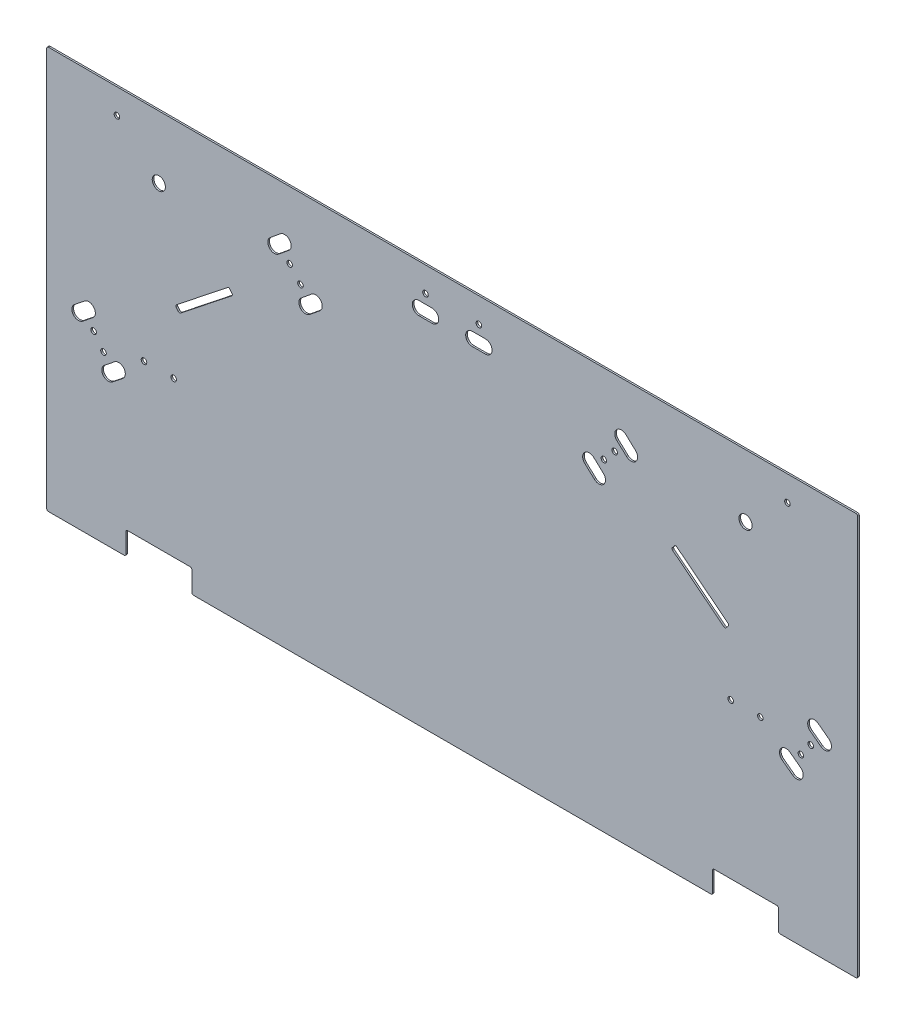
SolidWorks part; units mm, degrees
material "PE High Density"
ref_plane "Front Plane" through (0, 0, 0) normal (0, 0, 1) x (1, 0, 0)
ref_plane "Top Plane" through (0, 0, 0) normal (0, 1, 0) x (1, 0, 0)
ref_plane "Right Plane" through (0, 0, 0) normal (1, 0, 0) x (0, 0, -1)
sketch "Sketch1" plane through (0, 0, 0) normal (0, 0, 1) x (1, 0, 0)
  line L1 (-781.05, 387.35) -> (781.05, 387.35)
  line L2 (-781.05, 387.35) -> (-781.05, -387.35)
  line L3 (-781.05, -387.35) -> (781.05, -387.35)
  line L4 (781.05, 387.35) -> (781.05, -387.35)
  line L5 (-781.05, 387.35) -> (781.05, -387.35) construction
  line L6 (-781.05, -387.35) -> (781.05, 387.35) construction
  line L7 (-533.6334, 78.9622) -> (-525.7417, 69.0118)
  line L8 (-542.925, 342.9) -> (-542.925, -501.65) construction
  line L9 (542.925, 342.9) -> (542.925, -501.65) construction
  line L11 (587.375, 342.9) -> (587.375, -501.65) construction
  line L12 (-587.375, 342.9) -> (-587.375, -501.65) construction
  line L21 (-628.65, -387.35) -> (-501.65, -387.35)
  line L22 (-628.65, -387.35) -> (-628.65, -342.9)
  line L23 (-628.65, -342.9) -> (-501.65, -342.9)
  line L24 (-501.65, -387.35) -> (-501.65, -342.9)
  line L25 (628.65, -387.35) -> (501.65, -387.35)
  line L26 (628.65, -387.35) -> (628.65, -342.9)
  line L27 (628.65, -342.9) -> (501.65, -342.9)
  line L28 (501.65, -387.35) -> (501.65, -342.9)
  line L32 (-525.7417, 69.0118) -> (-422.2573, 151.0856)
  line L33 (-422.2573, 151.0856) -> (-430.149, 161.036)
  line L34 (-430.149, 161.036) -> (-533.6334, 78.9622)
  line L36 (525.8301, 69.1038) -> (422.2669, 151.078)
  line L37 (422.2669, 151.078) -> (430.149, 161.036)
  line L38 (430.149, 161.036) -> (533.7123, 79.0618)
  line L39 (533.7123, 79.0618) -> (525.8301, 69.1038)
  circle A0 centre (-51.435, 339.4592) radius 5.3578
  circle A1 centre (51.435, 339.3385) radius 5.3578
  circle A6 centre (-645.795, 339.09) radius 5.3578
  circle A7 centre (645.795, 339.09) radius 5.3578
  circle A11 centre (536.575, -44.45) radius 5.3578
  circle A12 centre (593.725, -44.45) radius 5.3578
  circle A13 centre (-593.725, -44.45) radius 5.3578
  circle A14 centre (-536.575, -44.45) radius 5.3578
  point P0 (0, 0)
  dimension "D3" = 10.7156
  dimension "D4" = 10.7156
  dimension "D7" = 729.615
  dimension "D8" = 729.615
  dimension "D19" = 135.255
  dimension "D20" = 48.26
  dimension "D21" = 10.7156
  dimension "D22" = 135.255
  dimension "D23" = 48.26
  dimension "D38" = 342.9
  dimension "D39" = 342.9
  dimension "D40" = 6.35
  dimension "D9" = 47.8908
  dimension "D14" = 350.901
  dimension "D24" = 10.7156
  dimension "D31" = 10.7156
  dimension "D32" = 10.7156
  dimension "D33" = 10.7156
  dimension "D34" = 10.7156
  dimension "D1" = 774.7
  dimension "D2" = 1562.1
  dimension "D10" = 48.0115
  dimension "D11" = 226.314
  dimension "D12" = 350.901
  dimension "D13" = 226.314
  dimension "D35" = 6.35
  dimension "D36" = 6.35
  dimension "D37" = 342.9
  dimension "D41" = 342.9
  dimension "D42" = 6.35
  dimension "D52" = 152.4
  dimension "D53" = 127
  dimension "D54" = 44.45
  dimension "D55" = 152.4
  dimension "D56" = 127
  dimension "D57" = 44.45
  dimension "D63" = 132.08
  dimension "D64" = 12.7
  dimension "D65" = 132.08
  dimension "D66" = 12.7
extrude "Boss-Extrude1" add sketch "Sketch1" along normal blind 3.175
sketch "Sketch2" plane through (0, 0, 3.175) normal (0, 0, 1) x (1, 0, 0)
  line L2 (781.05, 387.35) -> (781.05, -387.35) construction
  line L3 (628.65, -387.35) -> (781.05, -387.35) construction
  line L4 (-781.05, 387.35) -> (781.05, 387.35) construction
  line L5 (-781.05, 387.35) -> (-781.05, -387.35) construction
  line L7 (-781.05, -387.35) -> (-628.65, -387.35) construction
  circle A0 centre (-313.055, 258.318) radius 5.3578
  circle A1 centre (-292.227, 234.3543) radius 5.3578
  circle A2 centre (-690.753, -42.672) radius 5.3578
  circle A3 centre (-671.703, -68.072) radius 5.3578
  circle A4 centre (292.227, 234.3543) radius 5.3578
  circle A5 centre (313.055, 258.318) radius 5.3578
  circle A6 centre (690.753, -42.672) radius 5.3578
  circle A7 centre (671.703, -68.072) radius 5.3578
  dimension "D1" = 10.7156
  dimension "D3" = 31.75
  dimension "D8" = 129.032
  dimension "D2" = 90.297
  dimension "D4" = 344.678
  dimension "D5" = 109.347
  dimension "D6" = 31.75
  dimension "D7" = 467.995
  dimension "D9" = 488.823
  dimension "D10" = 467.995
  dimension "D11" = 488.823
  dimension "D12" = 129.032
  dimension "D13" = 31.75
  dimension "D14" = 90.297
  dimension "D15" = 109.347
  dimension "D16" = 344.678
  dimension "D17" = 31.75
extrude "Cut-Extrude1" cut sketch "Sketch2" against normal through all
sketch "Sketch3" plane through (0, 0, 3.175) normal (0, 0, 1) x (1, 0, 0)
  line L0 (-64.135, 308.9792) -> (-38.735, 308.9792) construction
  line L1 (-64.135, 321.6792) -> (-38.735, 321.6792)
  line L2 (-64.135, 296.2792) -> (-38.735, 296.2792)
  line L3 (38.735, 308.9792) -> (64.135, 308.9792) construction
  line L4 (38.735, 321.6792) -> (64.135, 321.6792)
  line L5 (38.735, 296.2792) -> (64.135, 296.2792)
  line L6 (-342.4859, 273.572) -> (-322.8733, 289.7122) construction
  line L7 (-350.556, 283.3784) -> (-330.9434, 299.5185)
  line L8 (-334.4159, 263.7657) -> (-314.8032, 279.9059)
  line L9 (-282.6651, 202.7491) -> (-263.0525, 218.8893) construction
  line L10 (-290.7352, 212.5554) -> (-271.1226, 228.6956)
  line L11 (-274.595, 192.9428) -> (-254.9824, 209.083)
  line L12 (-719.9479, -26.9932) -> (-700.1126, -11.1275) construction
  line L13 (-727.8807, -17.0755) -> (-708.0454, -1.2098)
  line L14 (-712.015, -36.9108) -> (-692.1797, -21.0451)
  line L15 (-662.2696, -99.5575) -> (-642.4343, -83.6918) construction
  line L16 (-670.2025, -89.6398) -> (-650.3672, -73.7742)
  line L17 (-654.3368, -109.4752) -> (-634.5015, -93.6095)
  line L18 (325.9271, 287.9302) -> (344.5749, 270.6843) construction
  line L19 (334.55, 297.2541) -> (353.1978, 280.0082)
  line L20 (317.3041, 278.6063) -> (335.952, 261.3604)
  line L21 (264.0577, 218.8893) -> (282.7056, 201.6434) construction
  line L22 (272.6807, 228.2132) -> (291.3285, 210.9673)
  line L23 (255.4348, 209.5654) -> (274.0826, 192.3195)
  line L24 (643.2495, -84.8267) -> (663.5646, -100.0734) construction
  line L25 (650.8729, -74.6692) -> (671.1879, -89.9158)
  line L26 (635.6262, -94.9843) -> (655.9413, -110.2309)
  line L27 (697.5841, -9.6895) -> (717.8992, -24.9361) construction
  line L28 (705.2074, 0.468) -> (725.5225, -14.7786)
  line L29 (689.9608, -19.847) -> (710.2758, -35.0936)
  line L30 (-781.05, 387.35) -> (781.05, 387.35) construction
  arc A0 (-64.135, 321.6792) -> (-64.135, 296.2792) centre (-64.135, 308.9792) ccw
  arc A1 (-38.735, 296.2792) -> (-38.735, 321.6792) centre (-38.735, 308.9792) ccw
  arc A2 (38.735, 321.6792) -> (38.735, 296.2792) centre (38.735, 308.9792) ccw
  arc A3 (64.135, 296.2792) -> (64.135, 321.6792) centre (64.135, 308.9792) ccw
  arc A4 (-350.556, 283.3784) -> (-334.4159, 263.7657) centre (-342.4859, 273.572) ccw
  arc A5 (-314.8032, 279.9059) -> (-330.9434, 299.5185) centre (-322.8733, 289.7122) ccw
  arc A6 (-290.7352, 212.5554) -> (-274.595, 192.9428) centre (-282.6651, 202.7491) ccw
  arc A7 (-254.9824, 209.083) -> (-271.1226, 228.6956) centre (-263.0525, 218.8893) ccw
  arc A8 (-727.8807, -17.0755) -> (-712.015, -36.9108) centre (-719.9479, -26.9932) ccw
  arc A9 (-692.1797, -21.0451) -> (-708.0454, -1.2098) centre (-700.1126, -11.1275) ccw
  arc A10 (-670.2025, -89.6398) -> (-654.3368, -109.4752) centre (-662.2696, -99.5575) ccw
  arc A11 (-634.5015, -93.6095) -> (-650.3672, -73.7742) centre (-642.4343, -83.6918) ccw
  arc A12 (334.55, 297.2541) -> (317.3041, 278.6063) centre (325.9271, 287.9302) ccw
  arc A13 (335.952, 261.3604) -> (353.1978, 280.0082) centre (344.5749, 270.6843) ccw
  arc A14 (272.6807, 228.2132) -> (255.4348, 209.5654) centre (264.0577, 218.8893) ccw
  arc A15 (274.0826, 192.3195) -> (291.3285, 210.9673) centre (282.7056, 201.6434) ccw
  arc A16 (650.8729, -74.6692) -> (635.6262, -94.9843) centre (643.2495, -84.8267) ccw
  arc A17 (655.9413, -110.2309) -> (671.1879, -89.9158) centre (663.5646, -100.0734) ccw
  arc A18 (705.2074, 0.468) -> (689.9608, -19.847) centre (697.5841, -9.6895) ccw
  arc A19 (710.2758, -35.0936) -> (725.5225, -14.7786) centre (717.8992, -24.9361) ccw
  circle A20 centre (-51.435, 339.4592) radius 5.3578 construction
  circle A21 centre (-313.055, 258.318) radius 5.3578 construction
  circle A22 centre (-292.227, 234.3543) radius 5.3578 construction
  circle A23 centre (-690.753, -42.672) radius 5.3578 construction
  circle A24 centre (-671.703, -68.072) radius 5.3578 construction
  circle A25 centre (292.227, 234.3543) radius 5.3578 construction
  circle A26 centre (313.055, 258.318) radius 5.3578 construction
  circle A27 centre (671.703, -68.072) radius 5.3578 construction
  circle A28 centre (690.753, -42.672) radius 5.3578 construction
  point P2 (-51.435, 308.9792)
  point P7 (51.435, 308.9792)
  point P14 (-332.6796, 281.6421)
  point P21 (-272.8588, 210.8192)
  point P28 (-710.0302, -19.0603)
  point P35 (-652.352, -91.6247)
  point P42 (335.251, 279.3073)
  point P49 (273.3817, 210.2664)
  point P56 (653.4071, -92.45)
  point P63 (707.7416, -17.3128)
  dimension "D3" = 17.78
  dimension "D5" = 17.78
  dimension "D1" = 25.4
  dimension "D2" = 25.4
  dimension "D4" = 17.78
  dimension "D6" = 17.78
  dimension "D7" = 17.78
  dimension "D8" = 17.78
  dimension "D9" = 17.78
  dimension "D10" = 17.78
  dimension "D11" = 17.78
extrude "Cut-Extrude2" cut sketch "Sketch3" against normal through all
fillet "Fillet1" radius 3.175 20 edges at (-525.7417, 69.0118, 1.5875) (-533.6334, 78.9622, 1.5875) (-430.149, 161.036, 1.5875) (-422.2573, 151.0856, 1.5875) (-628.65, -342.9, 1.5875) (-501.65, -342.9, 1.5875) (628.65, -342.9, 1.5875) (501.65, -342.9, 1.5875) (525.8301, 69.1038, 1.5875) (533.7123, 79.0618, 1.5875) (430.149, 161.036, 1.5875) (422.2669, 151.078, 1.5875) (-781.05, 387.35, 1.5875) (-781.05, -387.35, 1.5875) (-628.65, -387.35, 1.5875) (-501.65, -387.35, 1.5875) (501.65, -387.35, 1.5875) (628.65, -387.35, 1.5875) (781.05, -387.35, 1.5875) (781.05, 387.35, 1.5875)
sketch "Sketch4" plane through (0, 0, 3.175) normal (0, 0, 1) x (1, 0, 0)
  line L0 (-777.875, 387.35) -> (777.875, 387.35) construction
  point P0 (-565.15, 266.7)
  point P1 (565.15, 266.7)
  dimension "D1" = 1130.3
  dimension "D2" = 565.15
  dimension "D3" = 120.65
hole_wizard "1 (1) Diameter Hole1" positions "Sketch5" profile "Sketch6" hole size "1" standard "ANSI Inch" end condition up to next
sketch "Sketch5" plane through (0, 0, 3.175) normal (0, 0, 1) x (1, 0, 0)
  point P0 (-565.15, 266.7)
  point P3 (565.15, 266.7)
sketch "Sketch6" plane through (-565.15, 266.7, 3.175) normal (1, 0, 0) x (0, -1, 0)
  line L0 (0, 0) -> (0, 3.175)
  line L1 (0, 3.175) -> (12.7, 3.175)
  line L2 (12.7, 3.175) -> (12.7, 0)
  line L5 (12.7, 0) -> (0, 0)
  line L11 (0, -6.35) -> (0, 107.95) construction
  dimension "Thru Hole Dia." = 25.4
  dimension "Thru Hole Depth" = 3.175
equation "\"D2@Sketch4\"=\"D1@Sketch4\"/2"
